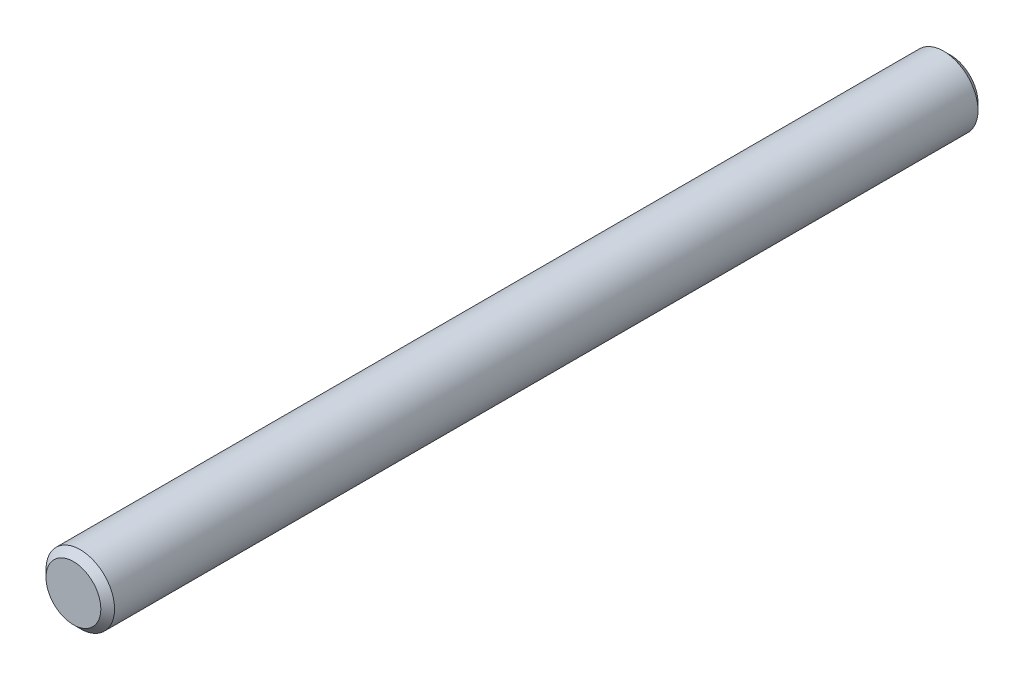
SolidWorks part; units mm, degrees
ref_plane "Front" through (0, 0, 0) normal (0, 0, 1) x (1, 0, 0)
ref_plane "Top" through (0, 0, 0) normal (0, 1, 0) x (1, 0, 0)
ref_plane "Right" through (0, 0, 0) normal (1, 0, 0) x (0, 0, -1)
sketch "Sketch1" plane through (0, 0, 0) normal (0, 0, 1) x (1, 0, 0)
  circle A0 centre (0, 0) radius 7.9375
  dimension "Dia" = 15.875
sketch "Sketch2" plane through (0, 0, 0) normal (1, 0, 0) x (0, 0, -1)
  line L0 (-101.6, 0) -> (101.6, 0) construction
  line L1 (-50.8, 7.9375) -> (-50.8, -7.9375) construction
  line L2 (8.7312, 0) -> (-8.7312, 0) construction
  line L3 (50.8, 7.9375) -> (50.8, -7.9375) construction
  line L4 (-101.6, 7.9375) -> (-101.6, -7.9375) construction
  line L5 (101.6, 7.9375) -> (101.6, -7.9375) construction
  point P3 (-50.8, 0)
  point P8 (0, 0)
  point P9 (50.8, 0)
  point P15 (-101.6, 0)
  point P18 (101.6, 0)
  dimension "D1" = 15.875
  dimension "LG" = 203.2
  dimension "D2" = 50.8
  dimension "D3" = 50.8
sketch "Sketch3" plane through (0, 0, 0) normal (0, 0, 1) x (1, 0, 0)
  circle A0 centre (0, 0) radius 7.9375
  dimension "D1" = 15.875
extrude "Boss-Extrude1" add sketch "Sketch3" along normal mid plane 203.2
chamfer "Chamfer1" distance 1.5875 angle 45 2 edges at (7.9375, 0, -101.6) (7.9375, 0, 101.6)
equation "\"D1@Sketch3\" = \"Dia@Sketch1\""
equation "\"D1@Boss-Extrude1\"=\"LG@Sketch2\""
equation "\"D1@Chamfer1\" = \"Dia@Sketch1\" * .1"
equation "\"D1@Sketch2\"=\"dia@sketch1\""
